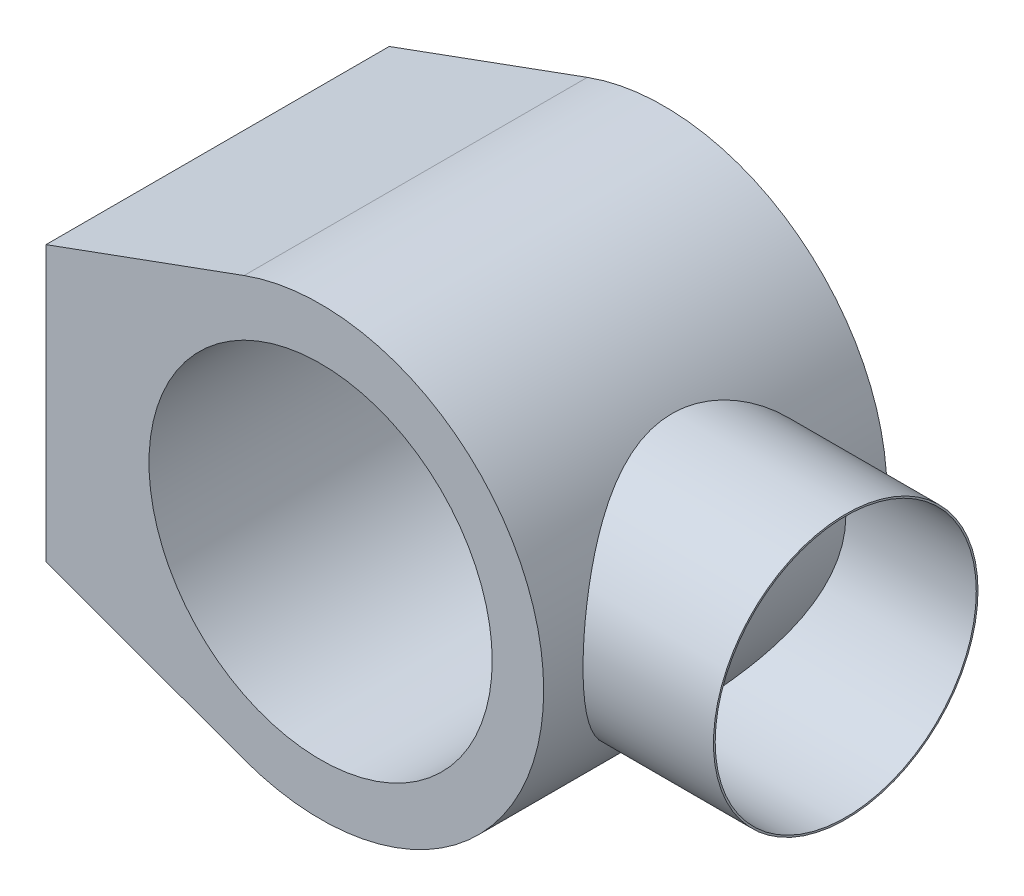
SolidWorks part; units mm, degrees
material "1023 Carbon Steel Sheet (SS)"
ref_plane "Front Plane" through (0, 0, 0) normal (0, 0, 1) x (1, 0, 0)
ref_plane "Top Plane" through (0, 0, 0) normal (0, 1, 0) x (1, 0, 0)
ref_plane "Right Plane" through (0, 0, 0) normal (1, 0, 0) x (0, 0, -1)
sketch "Sketch1" plane through (0, 0, 0) normal (0, 0, 1) x (1, 0, 0)
  line L0 (-80, 40) -> (-80, -40)
  line L1 (-80, 40) -> (-22.2817, 61.0617)
  line L2 (-80, -40) -> (-22.2817, -61.0617)
  arc A0 (-22.2817, -61.0617) -> (-22.2817, 61.0617) centre (0, 0) ccw
  circle A1 centre (0, 0) radius 50
  point P7 (-80, 0)
  dimension "D1" = 80
  dimension "D2" = 100
  dimension "D3" = 130
  dimension "D4" = 80
extrude "Boss-Extrude1" add sketch "Sketch1" along normal mid plane 100
ref_plane "Plane1" through (120, 0, 0) normal (1, 0, 0) x (0, 0, -1)
ref_plane "Plane2" through (103, 0, 0) normal (1, 0, 0) x (0, 0, -1)
sketch "Sketch2" plane through (103, 0, 0) normal (1, 0, 0) x (0, 0, -1)
  circle A0 centre (0, 0) radius 38.535
  circle A1 centre (0, 0) radius 38.035
  dimension "D1" = 77.07
  dimension "D2" = 76.07
extrude "Boss-Extrude2" add sketch "Sketch2" against normal up to next
sketch "Sketch3" plane through (103, 0, 0) normal (1, 0, 0) x (0, 0, -1)
  line L0 (15.724, -2.5) -> (8.724, 2.5) construction
  line L1 (1.5, 15.724) -> (-1.5, 15.724)
  line L2 (2.5, 14.724) -> (2.5, 9.724)
  line L3 (1.5, 8.724) -> (-1.5, 8.724)
  line L4 (-2.5, 14.724) -> (-2.5, 9.724)
  line L5 (2.5, 15.724) -> (-2.5, 8.724) construction
  line L6 (2.5, 8.724) -> (-2.5, 15.724) construction
  line L7 (8.724, -2.5) -> (15.724, 2.5) construction
  line L8 (14.724, -2.5) -> (9.724, -2.5)
  line L9 (15.724, -1.5) -> (15.724, 1.5)
  line L10 (14.724, 2.5) -> (9.724, 2.5)
  line L11 (8.724, -1.5) -> (8.724, 1.5)
  line L12 (-2.5, -15.724) -> (2.5, -8.724) construction
  line L13 (-2.5, -8.724) -> (2.5, -15.724) construction
  line L14 (-2.5, -14.724) -> (-2.5, -9.724)
  line L15 (-1.5, -15.724) -> (1.5, -15.724)
  line L16 (2.5, -14.724) -> (2.5, -9.724)
  line L17 (-1.5, -8.724) -> (1.5, -8.724)
  line L18 (-15.724, 2.5) -> (-8.724, -2.5) construction
  line L19 (-8.724, 2.5) -> (-15.724, -2.5) construction
  line L20 (-14.724, 2.5) -> (-9.724, 2.5)
  line L21 (-15.724, 1.5) -> (-15.724, -1.5)
  line L22 (-14.724, -2.5) -> (-9.724, -2.5)
  line L23 (-8.724, 1.5) -> (-8.724, -1.5)
  arc A0 (-2.5, -9.724) -> (-1.5, -8.724) centre (-1.5, -9.724) cw
  arc A1 (-1.5, -15.724) -> (-2.5, -14.724) centre (-1.5, -14.724) cw
  arc A2 (2.5, -14.724) -> (1.5, -15.724) centre (1.5, -14.724) cw
  arc A3 (2.5, -9.724) -> (1.5, -8.724) centre (1.5, -9.724) ccw
  arc A4 (-15.724, 1.5) -> (-14.724, 2.5) centre (-14.724, 1.5) cw
  arc A5 (-14.724, -2.5) -> (-15.724, -1.5) centre (-14.724, -1.5) cw
  arc A6 (-8.724, -1.5) -> (-9.724, -2.5) centre (-9.724, -1.5) cw
  arc A7 (-9.724, 2.5) -> (-8.724, 1.5) centre (-9.724, 1.5) cw
  arc A8 (8.724, 1.5) -> (9.724, 2.5) centre (9.724, 1.5) cw
  arc A9 (9.724, -2.5) -> (8.724, -1.5) centre (9.724, -1.5) cw
  arc A10 (15.724, -1.5) -> (14.724, -2.5) centre (14.724, -1.5) cw
  arc A11 (15.724, 1.5) -> (14.724, 2.5) centre (14.724, 1.5) ccw
  arc A12 (-2.5, 14.724) -> (-1.5, 15.724) centre (-1.5, 14.724) cw
  arc A13 (-1.5, 8.724) -> (-2.5, 9.724) centre (-1.5, 9.724) cw
  arc A14 (2.5, 9.724) -> (1.5, 8.724) centre (1.5, 9.724) cw
  arc A15 (2.5, 14.724) -> (1.5, 15.724) centre (1.5, 14.724) ccw
  point P0 (0, 12.224)
  point P5 (-7.0142, 5.8339)
  point P10 (-19.2382, -6.3901)
  point P19 (0, 0)
  dimension "D7" = 1
  dimension "D1" = 7
  dimension "D2" = 5
  dimension "D3" = 8.724
  dimension "D4" = 17.448
  dimension "D5" = 17.448
  dimension "D6" = 8.724
curve "Curve1"
